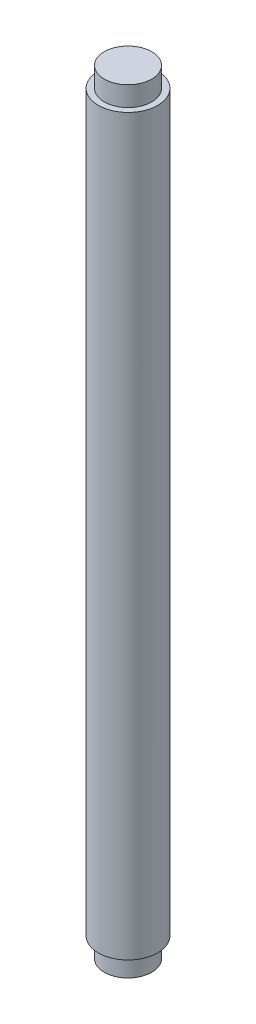
SolidWorks part; units mm, degrees
material "AISI 1020"
ref_plane "Front Plane" through (0, 0, 0) normal (0, 0, 1) x (1, 0, 0)
ref_plane "Top Plane" through (0, 0, 0) normal (0, 1, 0) x (1, 0, 0)
ref_plane "Right Plane" through (0, 0, 0) normal (1, 0, 0) x (0, 0, -1)
sketch "Sketch1" plane through (0, 0, 0) normal (0, 1, 0) x (1, 0, 0)
  circle A0 centre (0, 0) radius 15
  dimension "D1" = 30
extrude "Boss-Extrude1" add sketch "Sketch1" along normal mid plane 391
ref_plane "Plane1" through (0, 0, 17.5) normal (0, 0, 1) x (1, 0, 0)
sketch "Sketch2" plane through (0, 195.5, 0) normal (0, 1, 0) x (1, 0, 0)
  circle A0 centre (0, 0) radius 12
  dimension "D1" = 24
extrude "Cut-Extrude1" cut sketch "Sketch2" against normal blind 10 flip side to cut
cosmetic thread "Cosmetic Thread1" parameters "D1"=10, "D2"=21.797
mirror "Mirror1" about plane through (0, 0, 0) normal (0, 1, 0) of "Cut-Extrude1"
sketch "Sketch15" plane through (0, -195.5, 0) normal (0, -1, 0) x (1, 0, 0)
  point P0 (0, 0)
hole_wizard "Ø13.5 (13.5) Diameter Hole1" positions "Sketch16" profile "Sketch17" hole size "Ø13.5" standard "ANSI Metric"
sketch "Sketch16" plane through (0, -195.5, 0) normal (0, -1, 0) x (-1, 0, 0)
  point P0 (0, 0)
sketch "Sketch17" plane through (0, -195.5, 0) normal (1, 0, 0) x (0, 0, -1)
  line L0 (0, 0) -> (0, 6.0558)
  line L1 (0, 6.0558) -> (6.75, 2)
  line L2 (6.75, 2) -> (6.75, 0)
  line L5 (6.75, 0) -> (0, 0)
  line L10 (0, 6.0558) -> (-6.75, 2) construction
  line L11 (0, -6.35) -> (0, 107.95) construction
  dimension "Hole Dia." = 13.5
  dimension "Hole Depth" = 2
  dimension "Drill Angle" = 118
